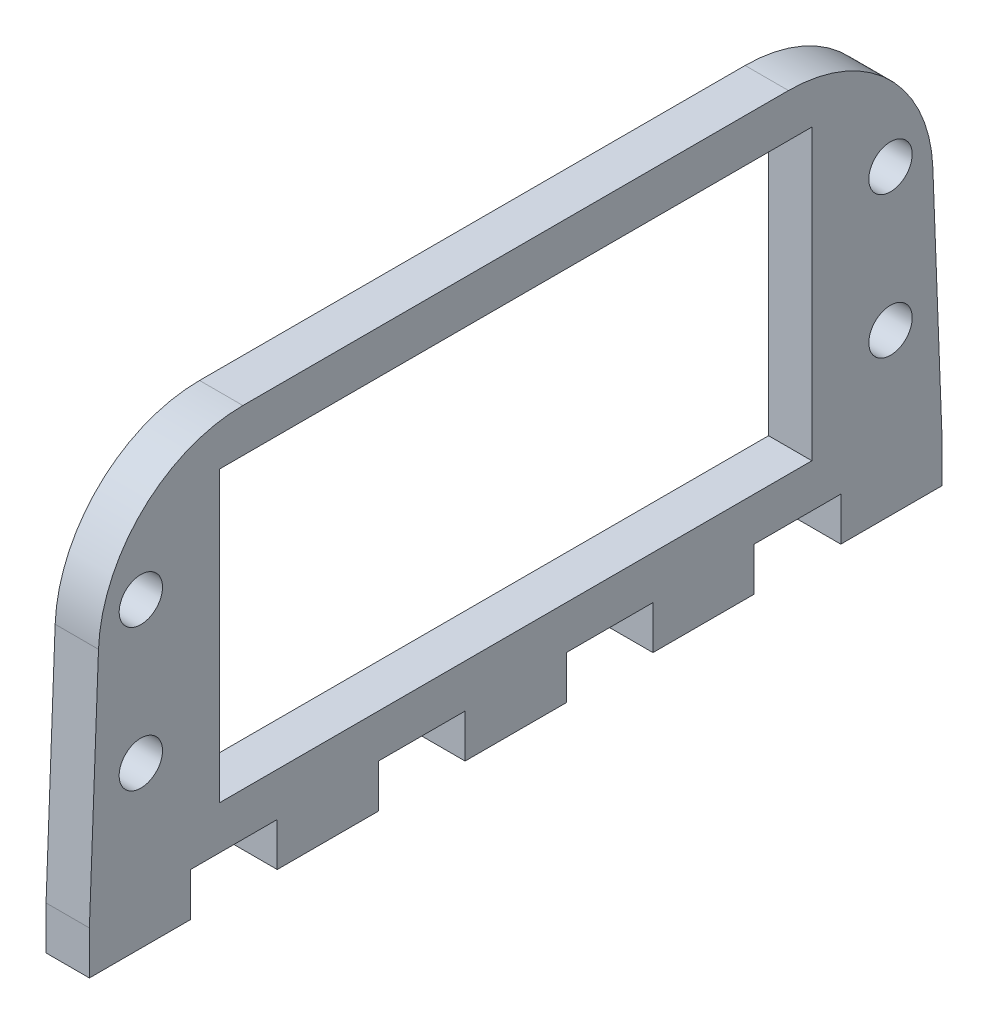
SolidWorks part; units mm, degrees
ref_plane "Front Plane" through (0, 0, 0) normal (0, 0, 1) x (1, 0, 0)
ref_plane "Top Plane" through (0, 0, 0) normal (0, 1, 0) x (1, 0, 0)
ref_plane "Right Plane" through (0, 0, 0) normal (1, 0, 0) x (0, 0, -1)
sketch "Sketch1" plane through (0, 0, 0) normal (1, 0, 0) x (0, 0, -1)
  line L0 (-33, 0) -> (-32, 26)
  line L1 (-32, 26) -> (25, 26)
  line L2 (25, 26) -> (26, 0)
  line L3 (26, 0) -> (26, -3)
  line L4 (26, -3) -> (19, -3)
  line L5 (19, -3) -> (19, 0)
  line L6 (19, 0) -> (13, 0)
  line L7 (13, 0) -> (13, -3)
  line L8 (13, -3) -> (6, -3)
  line L9 (6, -3) -> (6, 0)
  line L10 (6, 0) -> (0, 0)
  line L11 (0, 0) -> (0, -3)
  line L12 (0, -3) -> (-7, -3)
  line L13 (-7, -3) -> (-7, 0)
  line L14 (-7, 0) -> (-13, 0)
  line L15 (-13, 0) -> (-13, -3)
  line L16 (-13, -3) -> (-20, -3)
  line L17 (-20, -3) -> (-20, 0)
  line L18 (-20, 0) -> (-26, 0)
  line L19 (-26, 0) -> (-26, -3)
  line L20 (-26, -3) -> (-33, -3)
  line L21 (-33, -3) -> (-33, 0)
  line L22 (-3.5, 13) -> (-3.5, 18.1865) construction
  line L23 (-24, 23) -> (17, 23)
  line L24 (-24, 23) -> (-24, 3)
  line L25 (-24, 3) -> (17, 3)
  line L26 (17, 23) -> (17, 3)
  line L27 (-24, 23) -> (17, 3) construction
  line L28 (-24, 3) -> (17, 23) construction
  line L29 (-3.5, 13) -> (1.6461, 13) construction
  circle A0 centre (22.44, 17.9) radius 1.5
  circle A1 centre (22.44, 8.1) radius 1.5
  circle A2 centre (-29.44, 17.9) radius 1.5
  circle A3 centre (-29.44, 8.1) radius 1.5
  point P23 (-3.5, 13)
  point P38 (-3.5, -3)
  dimension "D7" = 3
  dimension "D8" = 3
  dimension "D1" = 7
  dimension "D2" = 3
  dimension "D3" = 6
  dimension "D4" = 20
  dimension "D5" = 41
  dimension "D6" = 3
  dimension "D9" = 5.1
  dimension "D10" = 5.44
  dimension "D12" = 57
extrude "Boss-Extrude1" add sketch "Sketch1" along normal blind 3
fillet "Fillet1" radius 10 2 edges at (1.5, 26, 32) (1.5, 26, -25)
